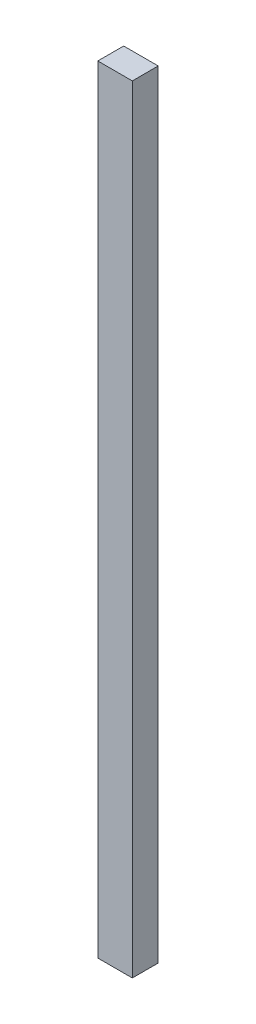
SolidWorks part; units mm, degrees
ref_plane "前视" through (0, 0, 0) normal (0, 0, 1) x (1, 0, 0)
ref_plane "上视" through (0, 0, 0) normal (0, 1, 0) x (1, 0, 0)
ref_plane "右视" through (0, 0, 0) normal (1, 0, 0) x (0, 0, -1)
sketch "草图1" plane through (0, 0, 0) normal (0, 0, 1) x (1, 0, 0)
  line L1 (0, 0) -> (4, 0)
  line L2 (0, 0) -> (0, 90)
  line L3 (0, 90) -> (4, 90)
  line L4 (4, 0) -> (4, 90)
  dimension "D1" = 90
  dimension "D2" = 4
extrude "凸台-拉伸1" add sketch "草图1" along normal blind 3
